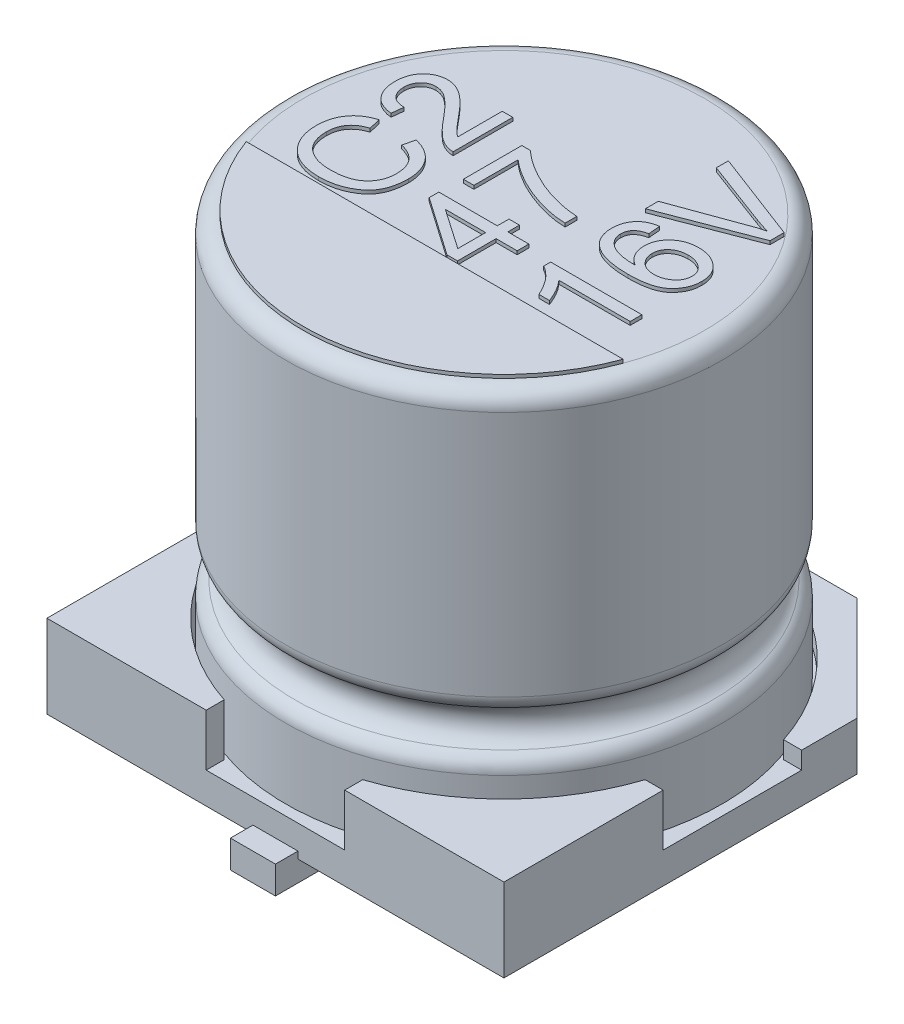
SolidWorks part; units mm, degrees
ref_plane "Plan de face" through (0, 0, 0) normal (0, 0, 1) x (1, 0, 0)
ref_plane "Plan de dessus" through (0, 0, 0) normal (0, 1, 0) x (1, 0, 0)
ref_plane "Plan de droite" through (0, 0, 0) normal (1, 0, 0) x (0, 0, -1)
sketch "Esquisse1" plane through (0, 0, 0) normal (0, 1, 0) x (1, 0, 0)
  line L1 (-3.3, -3.3) -> (3.3, -3.3)
  line L2 (-3.3, -3.3) -> (-3.3, 3.3)
  line L3 (-3.3, 3.3) -> (3.3, 3.3)
  line L4 (3.3, -3.3) -> (3.3, 3.3)
  line L5 (-3.3, -3.3) -> (3.3, 3.3) construction
  line L6 (-3.3, 3.3) -> (3.3, -3.3) construction
  point P0 (0, 0)
  dimension "D1" = 6.6
extrude "Boss.-Extru.1" add sketch "Esquisse1" along normal blind 1.2
sketch "Esquisse2" plane through (0, 1.2, 0) normal (0, 1, 0) x (1, 0, 0)
  line L0 (-3.3, 3.3) -> (-3.3, -3.3) construction
  line L1 (3.3, -1) -> (-3.3, -1)
  line L2 (3.3, -1) -> (3.3, 1)
  line L3 (3.3, 1) -> (-3.3, 1)
  line L4 (-3.3, -1) -> (-3.3, 1)
  line L5 (3.3, -1) -> (-3.3, 1) construction
  line L6 (3.3, 1) -> (-3.3, -1) construction
  line L7 (3.3, 3.3) -> (-3.3, 3.3) construction
  line L8 (-1, -3.3) -> (1, -3.3)
  line L9 (-1, -3.3) -> (-1, 3.3)
  line L10 (-1, 3.3) -> (1, 3.3)
  line L11 (1, -3.3) -> (1, 3.3)
  line L12 (-1, -3.3) -> (1, 3.3) construction
  line L13 (-1, 3.3) -> (1, -3.3) construction
  circle A0 centre (0, 0) radius 3.2
  line M1 (3.3, -3.3) -> (3.3, 3.3)
  line M2 (3.3, 3.3) -> (-3.3, 3.3)
  line M3 (-3.3, 3.3) -> (-3.3, -3.3)
  line M4 (-3.3, -3.3) -> (3.3, -3.3)
  dimension "D2" = 6.4
  dimension "D1" = 2
extrude "Enlèv. mat.-Extru.1" cut sketch "Esquisse2" against normal blind 0.75 contours A0 L3 L1 M3 | A0 L11 L9 M2 | A0 L1 L3 M1 | A0 L9 L11 M4
sketch "Esquisse3" plane through (0, 1.2, 0) normal (0, 1, 0) x (1, 0, 0)
  line L1 (-3.3, 0) -> (3.3, 0)
  line L2 (-3.3, 0) -> (-3.3, 3.3)
  line L3 (-3.3, 3.3) -> (3.3, 3.3)
  line L4 (3.3, 0) -> (3.3, 3.3)
extrude "Enlèv. mat.-Extru.2" cut sketch "Esquisse3" against normal blind 0.5
chamfer "Chanfrein1" distance 1.5 angle 45 2 edges at (3.3, 0.35, -3.3) (-3.3, 0.35, -3.3)
sketch "Esquisse4" plane through (0, 0, 0) normal (1, 0, 0) x (0, 0, -1)
  line L0 (-1, 0.45) -> (1, 0.45) construction
  line L1 (0, 0.45) -> (0, 6.25) construction
  line L2 (0, 6.25) -> (-2.9, 6.25)
  line L3 (0, 0.45) -> (-3.15, 0.45)
  line L4 (-3.15, 0.45) -> (-3.15, 1.4601)
  line L5 (-3.15, 6) -> (-3.15, 2.4399)
  line L6 (0, 0.45) -> (0, 6.25)
  arc A0 (-3.15, 1.4601) -> (-3.0136, 1.6828) centre (-2.9, 1.4601) cw
  arc A1 (-3.15, 2.4399) -> (-3.0136, 2.2172) centre (-2.9, 2.4399) ccw
  arc A2 (-3.0136, 1.6828) -> (-3.0136, 2.2172) centre (-3.15, 1.95) ccw
  arc A3 (-2.9, 6.25) -> (-3.15, 6) centre (-2.9, 6) ccw
  dimension "D1" = 0.25
  dimension "D3" = 0.3
  dimension "D5" = 0.25
  dimension "D2" = 5.8
  dimension "D4" = 6.3
  dimension "D6" = 1.5
revolve "Révolution1" add sketch "Esquisse4" angle 360 about L1
sketch "Esquisse5" plane through (0, 0, 0) normal (0, -1, 0) x (1, 0, 0)
  line L0 (-3.3, 3.3) -> (3.3, 3.3) construction
  line L1 (-0.325, 3.625) -> (0.325, 3.625)
  line L2 (-0.325, 3.625) -> (-0.325, 2.975)
  line L3 (-0.325, 2.975) -> (0.325, 2.975)
  line L4 (0.325, 3.625) -> (0.325, 2.975)
  line L5 (-0.325, 3.625) -> (0.325, 2.975) construction
  line L6 (-0.325, 2.975) -> (0.325, 3.625) construction
  line L7 (1.8, -3.3) -> (-1.8, -3.3) construction
  line L8 (-0.325, -3.625) -> (0.325, -3.625)
  line L9 (-0.325, -3.625) -> (-0.325, -2.975)
  line L10 (-0.325, -2.975) -> (0.325, -2.975)
  line L11 (0.325, -3.625) -> (0.325, -2.975)
  line L12 (-0.325, -3.625) -> (0.325, -2.975) construction
  line L13 (-0.325, -2.975) -> (0.325, -3.625) construction
  point P0 (0, 3.3)
  point P7 (0, -3.3)
  dimension "D1" = 0.65
extrude "Boss.-Extru.2" add sketch "Esquisse5" along normal blind 0.3 and the other way blind 0.1 separate body
sketch "Esquisse6" plane through (0, 0, 0) normal (0, -1, 0) x (1, 0, 0)
  line L1 (-2, -2) -> (2, -2) construction
  line L2 (-2, -2) -> (-2, 2) construction
  line L3 (-2, 2) -> (2, 2) construction
  line L4 (2, -2) -> (2, 2) construction
  line L5 (-2, -2) -> (2, 2) construction
  line L6 (-2, 2) -> (2, -2) construction
  circle A0 centre (-2, 2) radius 0.5
  circle A1 centre (2, 2) radius 0.5
  circle A2 centre (2, -2) radius 0.5
  circle A3 centre (-2, -2) radius 0.5
  point P0 (0, 0)
  dimension "D2" = 1
  dimension "D1" = 4
extrude "Boss.-Extru.3" add sketch "Esquisse6" along normal blind 0.3
sketch "Esquisse7" plane through (0, 6.25, 0) normal (0, 1, 0) x (1, 0, 0)
  line L0 (-2.7221, -1) -> (2.7221, -1)
  line L2 (0.6, 1.4825) -> (0.6, -1) construction
  line L3 (2.3, 1.4825) -> (2.3, -1) construction
  line L4 (-1.1007, 1.7727) -> (-1.1007, -1) construction
  circle A0 centre (0, 0) radius 2.9 construction
  circle A3 centre (0, 0) radius 2.9
  arc A4 (-2.7221, -1) -> (2.7221, -1) centre (0, 0) ccw
  text T1 "47" font "@Arial Unicode MS" height 1.3
  text T2 "16V" font "@Arial Unicode MS" height 1.3
  text T3 "C2" font "@Arial Unicode MS" height 1.3
  dimension "D1" = 1
  dimension "D2" = 1.7007
  dimension "D3" = 1.1007
  dimension "D4" = 1.7
  dimension "D5" = 0
extrude "Boss.-Extru.4" add sketch "Esquisse7" along normal blind 0.05 separate body
